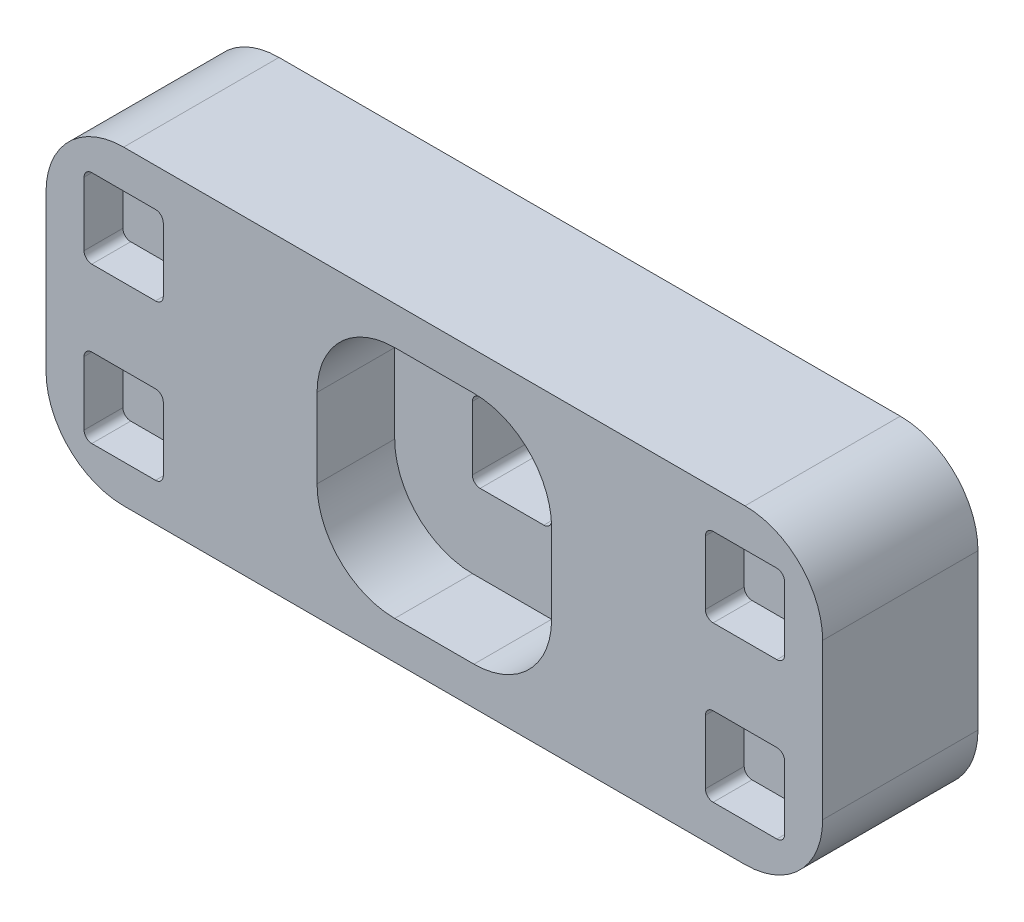
SolidWorks part; units mm, degrees
ref_plane "正面" through (0, 0, 0) normal (0, 0, 1) x (1, 0, 0)
ref_plane "平面" through (0, 0, 0) normal (0, 1, 0) x (1, 0, 0)
ref_plane "右側面" through (0, 0, 0) normal (1, 0, 0) x (0, 0, -1)
sketch "ｽｹｯﾁ1" plane through (0, 0, 0) normal (0, 0, 1) x (1, 0, 0)
  line L1 (-50, -20) -> (50, -20)
  line L2 (-50, -20) -> (-50, 20)
  line L3 (-50, 20) -> (50, 20)
  line L4 (50, -20) -> (50, 20)
  line L5 (-50, -20) -> (50, 20) construction
  line L6 (-50, 20) -> (50, -20) construction
  point P0 (0, 0)
  dimension "D1" = 100
  dimension "D2" = 40
extrude "ﾎﾞｽ - 押し出し1" add sketch "ｽｹｯﾁ1" along normal blind 20
fillet "ﾌｨﾚｯﾄ2" radius 10 4 edges at (50, -20, 10) (50, 20, 10) (-50, -20, 10) (-50, 20, 10)
sketch "ｽｹｯﾁ2" plane through (0, 0, 20) normal (0, 0, 1) x (1, 0, 0)
  line L1 (-5.1, -15.1) -> (5.1, -15.1)
  line L2 (-15.1, -5.1) -> (-15.1, 5.1)
  line L3 (-5.1, 15.1) -> (5.1, 15.1)
  line L4 (15.1, -5.1) -> (15.1, 5.1)
  line L5 (-15.1, -15.1) -> (15.1, 15.1) construction
  line L6 (-15.1, 15.1) -> (15.1, -15.1) construction
  arc A0 (-5.1, -15.1) -> (-15.1, -5.1) centre (-5.1, -5.1) cw
  arc A1 (5.1, -15.1) -> (15.1, -5.1) centre (5.1, -5.1) ccw
  arc A2 (5.1, 15.1) -> (15.1, 5.1) centre (5.1, 5.1) cw
  arc A3 (-15.1, 5.1) -> (-5.1, 15.1) centre (-5.1, 5.1) cw
  point P0 (0, 0)
  dimension "D3" = 10
  dimension "D1" = 30.2
  dimension "D2" = 30.2
extrude "ｶｯﾄ - 押し出し1" cut sketch "ｽｹｯﾁ2" against normal blind 10
sketch "ｽｹｯﾁ3" plane through (0, 0, 10) normal (0, 0, 1) x (1, 0, 0)
  line L1 (-4.1, -5.1) -> (4.1, -5.1)
  line L2 (-5.1, -4.1) -> (-5.1, 4.1)
  line L3 (-4.1, 5.1) -> (4.1, 5.1)
  line L4 (5.1, -4.1) -> (5.1, 4.1)
  line L5 (-5.1, -5.1) -> (5.1, 5.1) construction
  line L6 (-5.1, 5.1) -> (5.1, -5.1) construction
  arc A0 (-4.1, -5.1) -> (-5.1, -4.1) centre (-4.1, -4.1) cw
  arc A1 (4.1, -5.1) -> (5.1, -4.1) centre (4.1, -4.1) ccw
  arc A2 (4.1, 5.1) -> (5.1, 4.1) centre (4.1, 4.1) cw
  arc A3 (-5.1, 4.1) -> (-4.1, 5.1) centre (-4.1, 4.1) cw
  point P0 (0, 0)
  dimension "D3" = 1
  dimension "D1" = 10.2
  dimension "D2" = 10.2
extrude "ｶｯﾄ - 押し出し2" cut sketch "ｽｹｯﾁ3" against normal through all
sketch "ｽｹｯﾁ4" plane through (0, 0, 20) normal (0, 0, 1) x (1, 0, 0)
  line L0 (0, 20) -> (0, -20) construction
  line L1 (40, 20) -> (-40, 20) construction
  line L2 (-40, -20) -> (40, -20) construction
  line L3 (-50, 0) -> (50, 0) construction
  line L4 (-50, 10) -> (-50, -10) construction
  line L5 (50, -10) -> (50, 10) construction
  line L6 (44.1, 15.1) -> (35.9, 15.1)
  line L7 (-44.1, 4.9) -> (-35.9, 4.9)
  line L8 (-45.1, 5.9) -> (-45.1, 14.1)
  line L9 (-44.1, 15.1) -> (-35.9, 15.1)
  line L10 (-34.9, 5.9) -> (-34.9, 14.1)
  line L11 (-45.1, 4.9) -> (-34.9, 15.1) construction
  line L12 (-45.1, 15.1) -> (-34.9, 4.9) construction
  line L13 (34.9, 5.9) -> (34.9, 14.1)
  line L14 (44.1, 4.9) -> (35.9, 4.9)
  line L15 (45.1, 5.9) -> (45.1, 14.1)
  line L16 (45.1, -5.9) -> (45.1, -14.1)
  line L17 (44.1, -4.9) -> (35.9, -4.9)
  line L18 (34.9, -5.9) -> (34.9, -14.1)
  line L19 (44.1, -15.1) -> (35.9, -15.1)
  line L20 (-44.1, -15.1) -> (-35.9, -15.1)
  line L21 (-34.9, -5.9) -> (-34.9, -14.1)
  line L22 (-44.1, -4.9) -> (-35.9, -4.9)
  line L23 (-45.1, -5.9) -> (-45.1, -14.1)
  arc A4 (-35.9, 4.9) -> (-34.9, 5.9) centre (-35.9, 5.9) ccw
  arc A5 (-44.1, 4.9) -> (-45.1, 5.9) centre (-44.1, 5.9) cw
  arc A6 (-45.1, 14.1) -> (-44.1, 15.1) centre (-44.1, 14.1) cw
  arc A7 (-35.9, 15.1) -> (-34.9, 14.1) centre (-35.9, 14.1) cw
  arc A8 (35.9, 15.1) -> (34.9, 14.1) centre (35.9, 14.1) ccw
  arc A9 (35.9, 4.9) -> (34.9, 5.9) centre (35.9, 5.9) cw
  arc A10 (44.1, 4.9) -> (45.1, 5.9) centre (44.1, 5.9) ccw
  arc A11 (45.1, 14.1) -> (44.1, 15.1) centre (44.1, 14.1) ccw
  arc A12 (45.1, -14.1) -> (44.1, -15.1) centre (44.1, -14.1) cw
  arc A13 (44.1, -4.9) -> (45.1, -5.9) centre (44.1, -5.9) cw
  arc A14 (35.9, -4.9) -> (34.9, -5.9) centre (35.9, -5.9) ccw
  arc A15 (35.9, -15.1) -> (34.9, -14.1) centre (35.9, -14.1) cw
  arc A16 (-35.9, -15.1) -> (-34.9, -14.1) centre (-35.9, -14.1) ccw
  arc A17 (-35.9, -4.9) -> (-34.9, -5.9) centre (-35.9, -5.9) cw
  arc A18 (-44.1, -4.9) -> (-45.1, -5.9) centre (-44.1, -5.9) ccw
  arc A19 (-45.1, -14.1) -> (-44.1, -15.1) centre (-44.1, -14.1) ccw
  point P12 (-40, 10)
  point P19 (-47.4955, 6.582)
  dimension "D1" = 10.2
  dimension "D5" = 1
  dimension "D2" = 10.2
  dimension "D3" = 10
  dimension "D4" = 10
extrude "ｶｯﾄ - 押し出し3" cut sketch "ｽｹｯﾁ4" against normal blind 5
sketch "ｽｹｯﾁ5" plane through (0, 0, 0) normal (0, 0, -1) x (-1, 0, 0)
  line L0 (-50, 0) -> (50, 0) construction
  line L1 (-50, -10) -> (-50, 10) construction
  line L2 (50, 10) -> (50, -10) construction
  line L4 (-39, -10.1) -> (-20.8, -10.1)
  line L5 (-40, -9.1) -> (-40, 9.1)
  line L6 (-39, 10.1) -> (-20.8, 10.1)
  line L7 (-19.8, -9.1) -> (-19.8, 9.1)
  line L8 (-40, -10.1) -> (-19.8, 10.1) construction
  line L9 (-40, 10.1) -> (-19.8, -10.1) construction
  line L10 (20.8, -10.1) -> (39, -10.1)
  line L11 (19.8, -9.1) -> (19.8, 9.1)
  line L12 (20.8, 10.1) -> (39, 10.1)
  line L13 (40, -9.1) -> (40, 9.1)
  line L14 (19.8, -10.1) -> (40, 10.1) construction
  line L15 (19.8, 10.1) -> (40, -10.1) construction
  arc A0 (19.8, 9.1) -> (20.8, 10.1) centre (20.8, 9.1) cw
  arc A1 (39, 10.1) -> (40, 9.1) centre (39, 9.1) cw
  arc A2 (39, -10.1) -> (40, -9.1) centre (39, -9.1) ccw
  arc A3 (20.8, -10.1) -> (19.8, -9.1) centre (20.8, -9.1) cw
  arc A4 (-39, -10.1) -> (-40, -9.1) centre (-39, -9.1) cw
  arc A5 (-20.8, -10.1) -> (-19.8, -9.1) centre (-20.8, -9.1) ccw
  arc A6 (-20.8, 10.1) -> (-19.8, 9.1) centre (-20.8, 9.1) cw
  arc A7 (-40, 9.1) -> (-39, 10.1) centre (-39, 9.1) cw
  point P6 (-29.9, 0)
  point P11 (29.9, 0)
  dimension "D7" = 1
  dimension "D1" = 20.2
  dimension "D2" = 20.2
  dimension "D3" = 20.2
  dimension "D4" = 20.2
  dimension "D5" = 10
  dimension "D6" = 10
extrude "ｶｯﾄ - 押し出し4" cut sketch "ｽｹｯﾁ5" against normal blind 10
